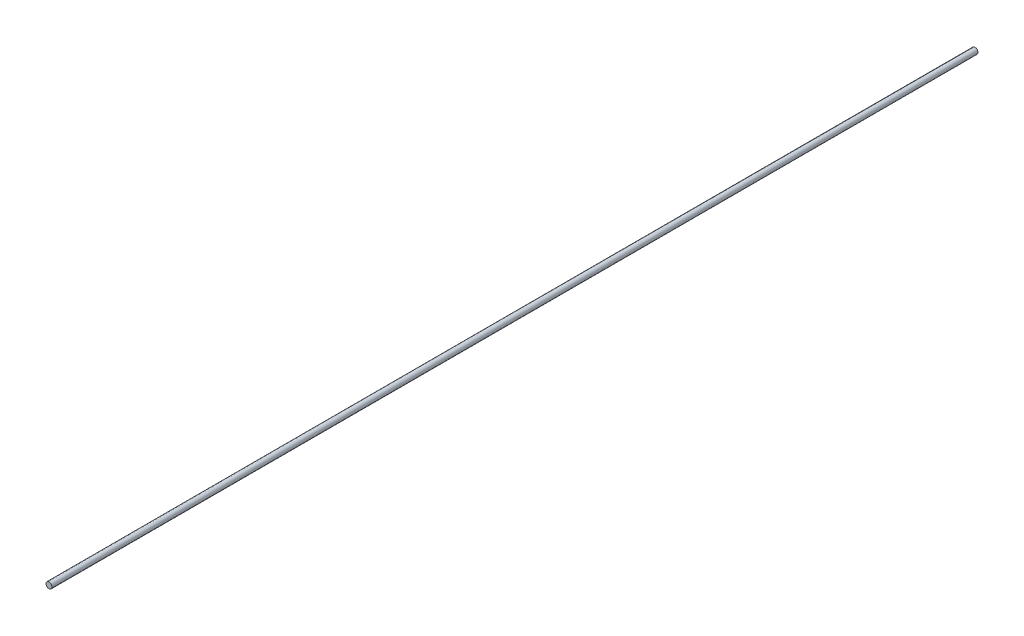
SolidWorks part; units mm, degrees
material "6061 Alloy"
ref_plane "Front Plane" through (0, 0, 0) normal (0, 0, 1) x (1, 0, 0)
ref_plane "Top Plane" through (0, 0, 0) normal (0, 1, 0) x (1, 0, 0)
ref_plane "Right Plane" through (0, 0, 0) normal (1, 0, 0) x (0, 0, -1)
sketch "Sketch1" plane through (0, 0, 0) normal (0, 0, 1) x (1, 0, 0)
  circle A0 centre (0, 0) radius 3.175
  dimension "D1" = 6.35
extrude "Boss-Extrude1" add sketch "Sketch1" along normal blind 990.6
